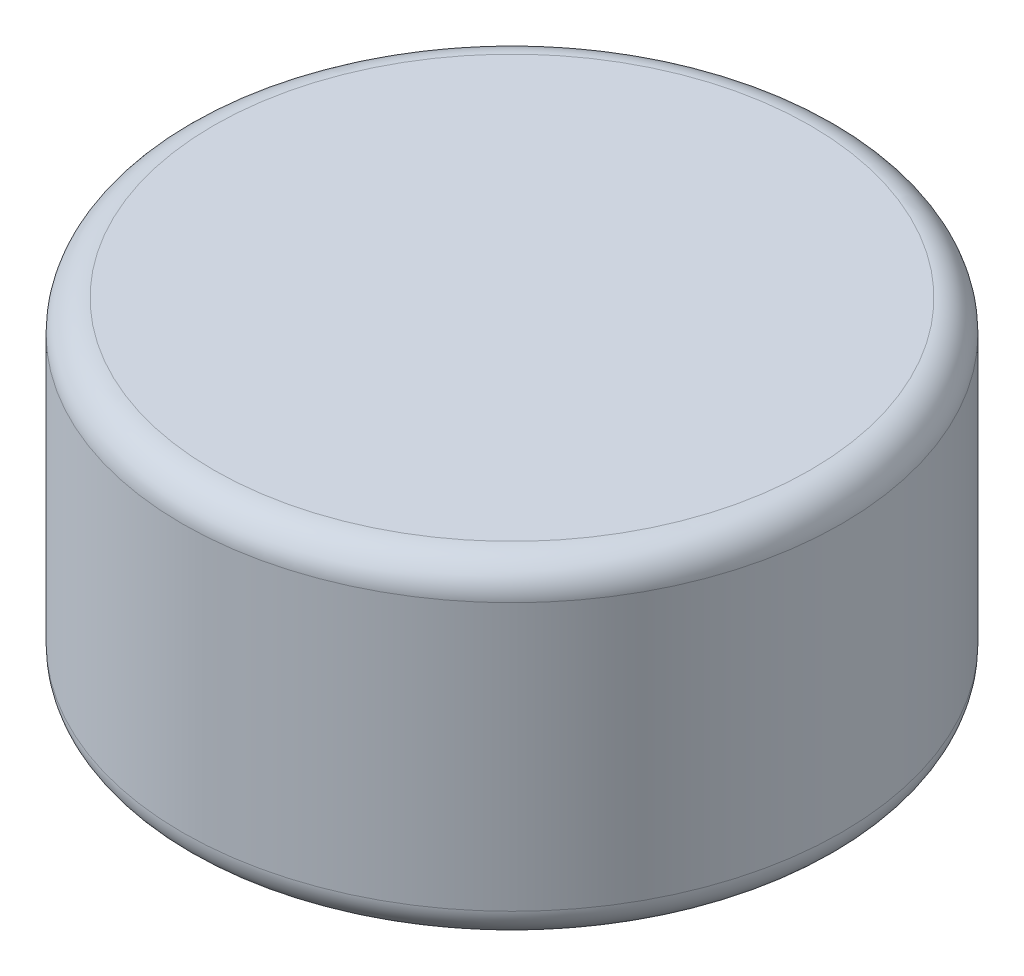
SolidWorks part; units mm, degrees
ref_plane "Front Plane" through (0, 0, 0) normal (0, 0, 1) x (1, 0, 0)
ref_plane "Top Plane" through (0, 0, 0) normal (0, 1, 0) x (1, 0, 0)
ref_plane "Right Plane" through (0, 0, 0) normal (1, 0, 0) x (0, 0, -1)
sketch "Sketch1" plane through (0, 0, 0) normal (0, 0, 1) x (1, 0, 0)
  line L1 (0, 0) -> (-3.175, 0)
  line L2 (0, 0) -> (0, 3.175)
  line L3 (0, 3.175) -> (-3.175, 3.175)
  line L4 (-3.175, 0) -> (-3.175, 3.175)
  dimension "D1" = 3.175
  dimension "D2" = 3.175
revolve "Revolve1" add sketch "Sketch1" angle 360 about L2
fillet "Fillet1" radius 0.3 2 edges at (3.175, 0, 0) (3.175, 3.175, 0)
